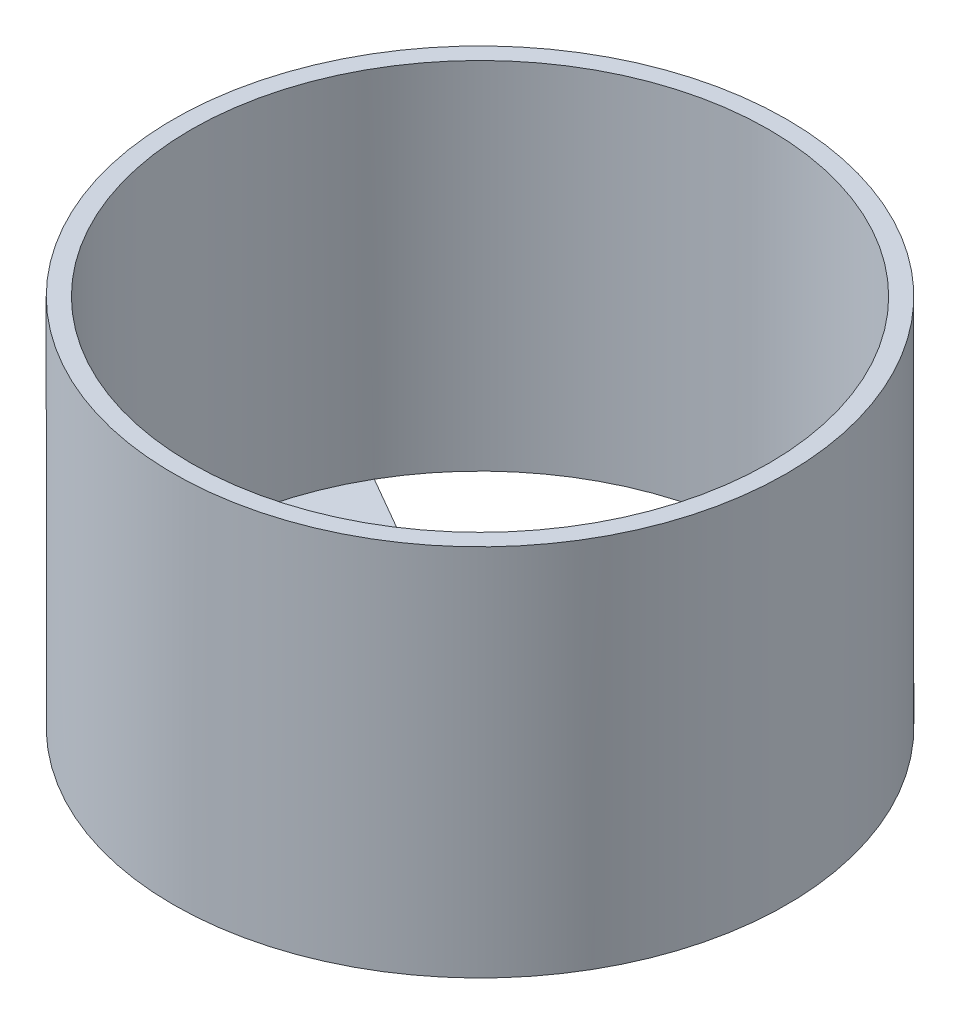
SolidWorks part; units mm, degrees
ref_plane "Front Plane" through (0, 0, 0) normal (0, 0, 1) x (1, 0, 0)
ref_plane "Top Plane" through (0, 0, 0) normal (0, 1, 0) x (1, 0, 0)
ref_plane "Right Plane" through (0, 0, 0) normal (1, 0, 0) x (0, 0, -1)
sketch "Sketch1" plane through (0, 0, 0) normal (0, 1, 0) x (1, 0, 0)
  circle A0 centre (0, 0) radius 41.275
  dimension "D1" = 82.55
extrude "Extrude-Thin1" add sketch "Sketch1" along normal blind 50.8 thin
sketch "Sketch2" plane through (0, 0, 0) normal (0, -1, 0) x (1, 0, 0)
  line L0 (0, -43.815) -> (0, 0)
  line L1 (0, 0) -> (-37.9449, -21.9075)
  arc A0 (0, -43.815) -> (-37.9449, -21.9075) centre (0, 0) ccw
  circle A1 centre (0, 0) radius 43.815 construction
  dimension "D1" = 60
extrude "Boss-Extrude1" add sketch "Sketch2" along normal blind 2.54
